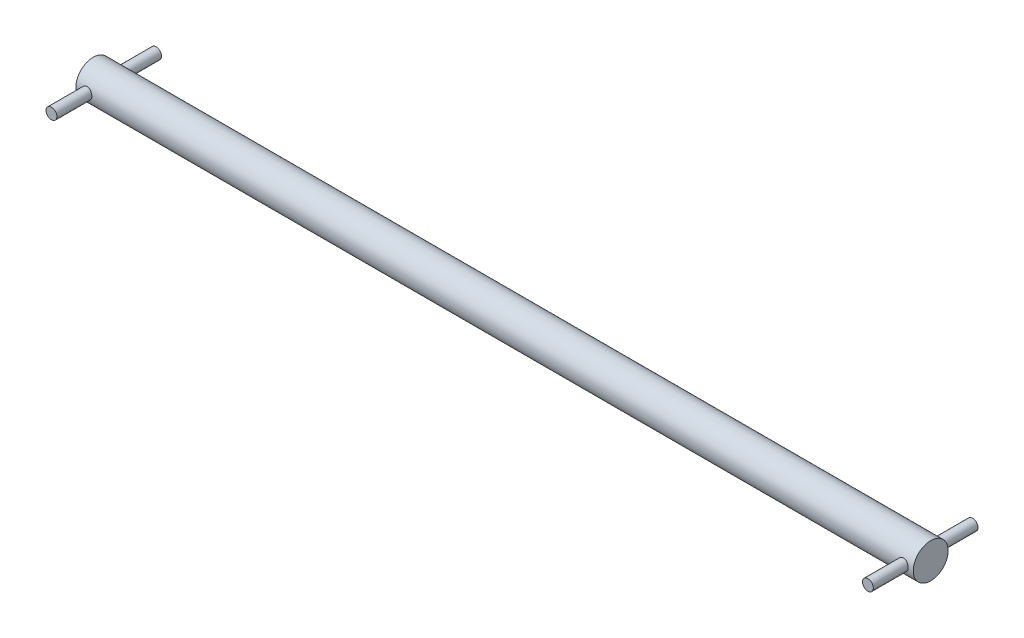
SolidWorks part; units mm, degrees
ref_plane "Front Plane" through (0, 0, 0) normal (0, 0, 1) x (1, 0, 0)
ref_plane "Top Plane" through (0, 0, 0) normal (0, 1, 0) x (1, 0, 0)
ref_plane "Right Plane" through (0, 0, 0) normal (1, 0, 0) x (0, 0, -1)
sketch "Sketch1" plane through (0, 0, 0) normal (1, 0, 0) x (0, 0, -1)
  circle A0 centre (0, 0) radius 12.7
  dimension "D1" = 25.4
extrude "Boss-Extrude1" add sketch "Sketch1" along normal blind 609.6
sketch "Sketch2" plane through (0, 0, 0) normal (0, 0, 1) x (1, 0, 0)
  line L0 (304.8, 12.7) -> (304.8, -12.7) construction
  line L1 (609.6, 12.7) -> (0, 12.7) construction
  line L2 (0, -12.7) -> (609.6, -12.7) construction
  line L3 (0, 12.7) -> (0, -12.7) construction
  circle A0 centre (7.62, 0) radius 3.9688
  circle A1 centre (601.98, 0) radius 3.9688
  dimension "D1" = 7.9375
  dimension "D2" = 7.62
extrude "Boss-Extrude2" add sketch "Sketch2" along normal mid plane 76.2
